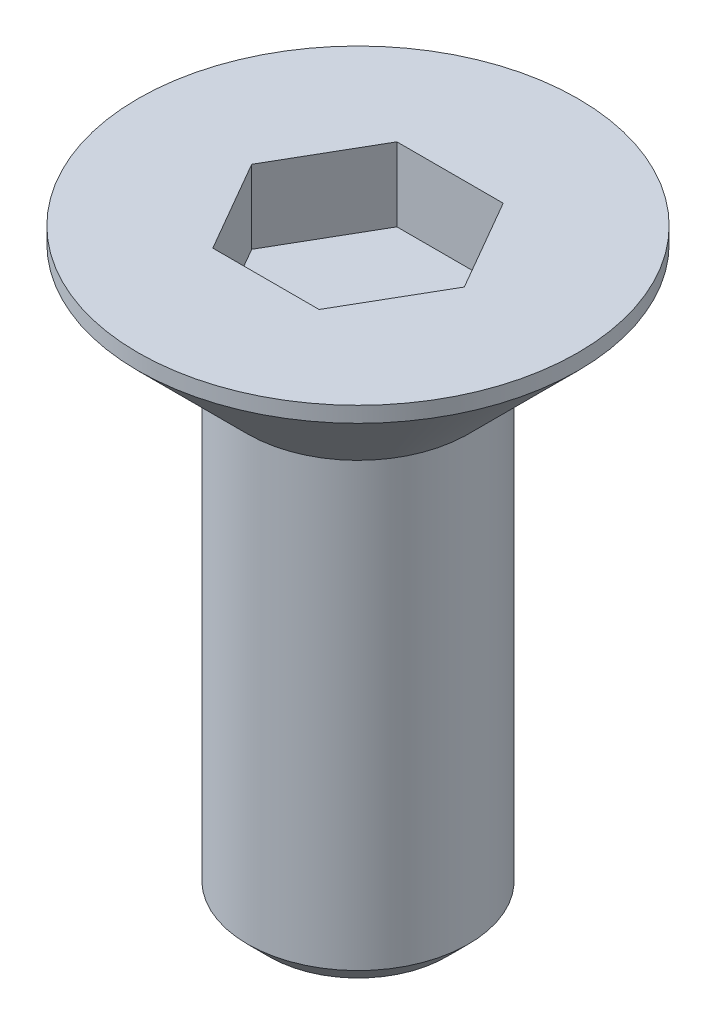
SolidWorks part; units mm, degrees
material "acero"
ref_plane "Alzado" through (0, 0, 0) normal (0, 0, 1) x (1, 0, 0)
ref_plane "Planta" through (0, 0, 0) normal (0, 1, 0) x (1, 0, 0)
ref_plane "Vista lateral" through (0, 0, 0) normal (1, 0, 0) x (0, 0, -1)
sketch "Croquis1" plane through (0, 0, 0) normal (0, 0, 1) x (1, 0, 0)
  line L0 (0, 0) -> (0, -60.9498) construction
  line L1 (0, 0) -> (3.2, 0)
  line L2 (1.5, -1.7) -> (3.2, 0)
  line L4 (1.5, -1.7) -> (1.5, -8)
  line L5 (1.5, -8) -> (0, -8)
  line L6 (0, -8) -> (0, 0)
  dimension "D1" = 8
  dimension "D2" = 45
  dimension "D3" = 1.7
  dimension "D4" = 3
revolve "Revolución1" add sketch "Croquis1" angle 360 about L0
chamfer "Chaflán2" distance 0.3 angle 45 1 edges at (0, 0, 3.2)
chamfer "Chaflán3" distance 0.3 angle 45 1 edges at (0, -8, 1.5)
sketch "Croquis3" plane through (0, 0, 0) normal (0, 1, 0) x (1, 0, 0)
  line L1 (-0.7217, 1.25) -> (-1.4434, 0)
  line L2 (-1.4434, 0) -> (-0.7217, -1.25)
  line L3 (-0.7217, -1.25) -> (0.7217, -1.25)
  line L4 (0.7217, -1.25) -> (1.4434, 0)
  line L5 (1.4434, 0) -> (0.7217, 1.25)
  line L6 (0.7217, 1.25) -> (-0.7217, 1.25)
  circle A0 centre (0, 0) radius 1.25 construction
  dimension "D1" = 2.5
extrude "Cortar-Extruir2" cut sketch "Croquis3" against normal blind 1
